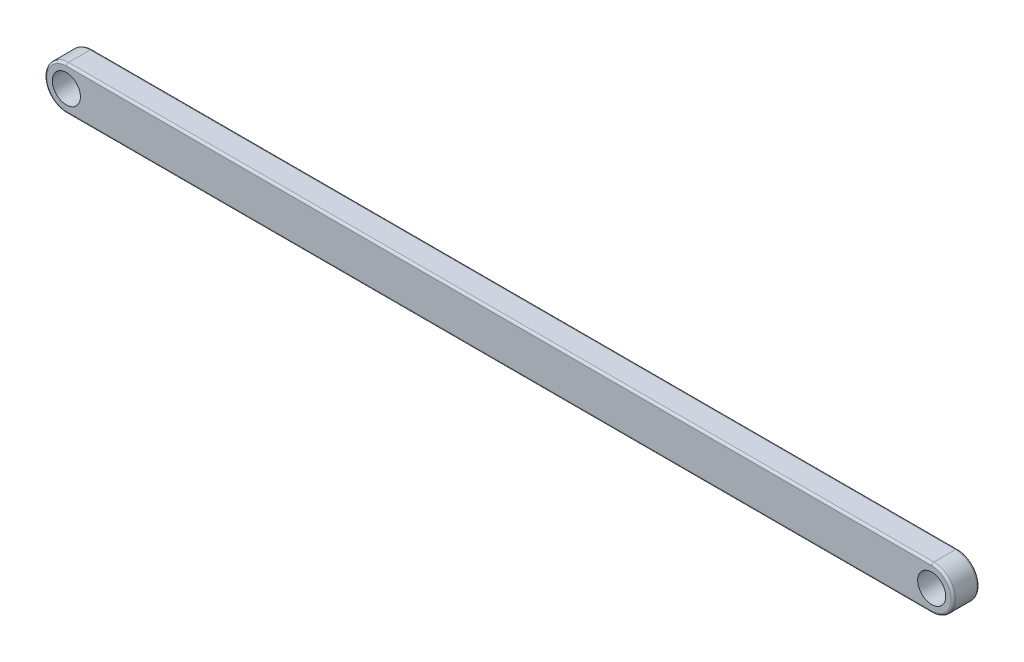
SolidWorks part; units mm, degrees
ref_plane "Front Plane" through (0, 0, 0) normal (0, 0, 1) x (1, 0, 0)
ref_plane "Top Plane" through (0, 0, 0) normal (0, 1, 0) x (1, 0, 0)
ref_plane "Right Plane" through (0, 0, 0) normal (1, 0, 0) x (0, 0, -1)
sketch "Sketch1" plane through (0, 0, 0) normal (0, 0, 1) x (1, 0, 0)
  line L0 (-50.2183, 0) -> (149.7817, 0) construction
  line L1 (-50.2183, 5) -> (149.7817, 5)
  line L2 (-50.2183, -5) -> (149.7817, -5)
  arc A0 (-50.2183, 5) -> (-50.2183, -5) centre (-50.2183, 0) ccw
  arc A1 (149.7817, -5) -> (149.7817, 5) centre (149.7817, 0) ccw
  circle A2 centre (-50.2183, 0) radius 3.25
  circle A3 centre (149.7817, 0) radius 3.25
  point P2 (49.7817, 0)
  dimension "D3" = 6.5
  dimension "D4" = 6.5
  dimension "D1" = 200
  dimension "D2" = 10
extrude "Boss-Extrude1" add sketch "Sketch1" along normal blind 6
fillet "Fillet1" radius 0.5 8 edges at (154.7817, 0, 0) (49.7817, -5, 0) (-55.2183, 0, 0) (154.7817, 0, 6) (49.7817, -5, 6) (-55.2183, 0, 6) (49.7817, 5, 0) (49.7817, 5, 6)
scale "缩放比例1" scale about centroid uniform scaling yes scale factor 2
